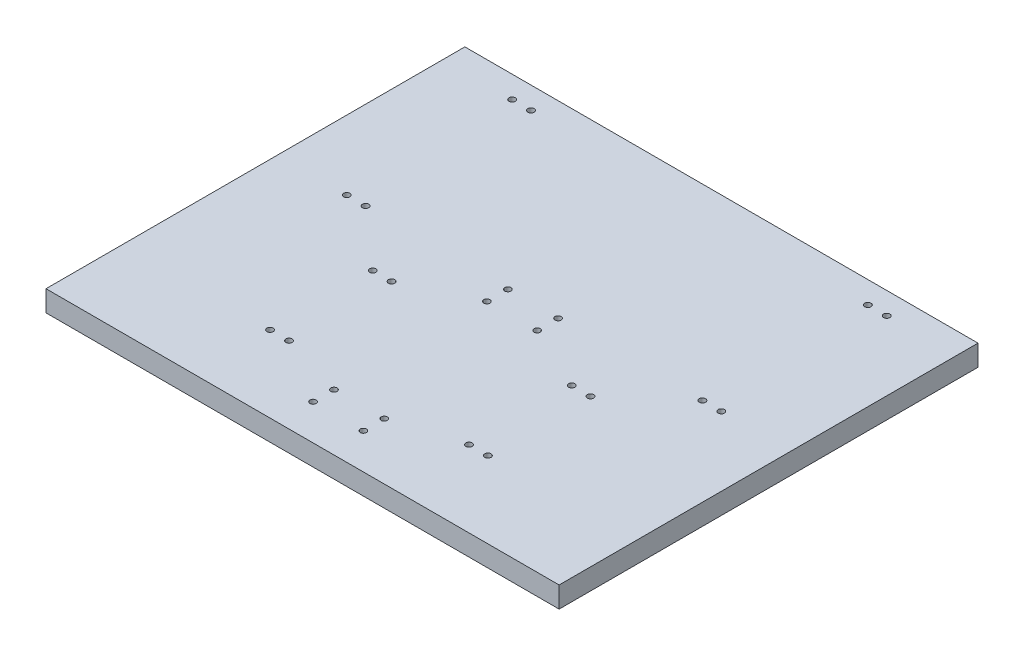
SolidWorks part; units mm, degrees
ref_plane "Front Plane" through (0, 0, 0) normal (0, 0, 1) x (1, 0, 0)
ref_plane "Top Plane" through (0, 0, 0) normal (0, 1, 0) x (1, 0, 0)
ref_plane "Right Plane" through (0, 0, 0) normal (1, 0, 0) x (0, 0, -1)
sketch "Sketch1" plane through (0, 0, 0) normal (0, 1, 0) x (1, 0, 0)
  line L0 (88.8314, 200) -> (88.8314, 0) construction
  line L1 (0, 0) -> (122.5, 0)
  line L2 (0, 0) -> (0, 200)
  line L3 (0, 200) -> (122.5, 200)
  line L4 (122.5, 0) -> (122.5, 200)
  line L5 (0, 175.2721) -> (122.5, 175.2721) construction
  line L6 (0, 123.5936) -> (122.5, 123.5936) construction
  dimension "D1" = 122.5
  dimension "D2" = 200
extrude "Boss-Extrude1" add sketch "Sketch1" along normal blind 10
sketch "Sketch4" plane through (0, 10, 0) normal (0, 1, 0) x (1, 0, 0)
  line L0 (0, 189.5) -> (122.5, 189.5) construction
  line L1 (0, 200) -> (0, 0) construction
  line L2 (122.5, 0) -> (122.5, 200) construction
  line L3 (0, 110.5) -> (122.5, 110.5) construction
  line L4 (37.575, 200) -> (37.575, 0) construction
  line L5 (122.5, 200) -> (0, 200) construction
  line L6 (0, 0) -> (122.5, 0) construction
  line L7 (75, 200) -> (75, 0) construction
  line L8 (0, 85.5) -> (122.5, 85.5) construction
  line L9 (0, 36.5) -> (122.5, 36.5) construction
  circle A0 centre (33.075, 189.5) radius 1.5
  circle A1 centre (42.075, 189.5) radius 1.5
  circle A2 centre (33.075, 110.5) radius 1.5
  circle A3 centre (42.075, 110.5) radius 1.5
  circle A4 centre (70.5, 85.5) radius 1.5
  circle A5 centre (79.5, 85.5) radius 1.5
  circle A6 centre (70.5, 36.5) radius 1.5
  circle A7 centre (79.5, 36.5) radius 1.5
  dimension "D6" = 3
  dimension "D1" = 10.5
  dimension "D2" = 79
  dimension "D3" = 37.575
  dimension "D4" = 4.5
  dimension "D5" = 4.5
  dimension "D7" = 75
  dimension "D8" = 49
  dimension "D9" = 25
  dimension "D10" = 4.5
  dimension "D11" = 4.5
extrude "Cut-Extrude2" cut sketch "Sketch4" against normal blind 10
mirror "Mirror1" about plane through (122.5, 10, 0) normal (-1, 0, 0) of bodies 103
sketch "Sketch5" plane through (0, 10, 0) normal (0, 1, 0) x (1, 0, 0)
  line L0 (0, 22) -> (245, 22) construction
  line L1 (0, 200) -> (0, 0) construction
  line L2 (245, 200) -> (245, 0) construction
  line L3 (0, 105) -> (245, 105) construction
  line L4 (245, 200) -> (0, 200) construction
  line L5 (0, 0) -> (245, 0) construction
  line L6 (122.5, 200) -> (122.5, 0) construction
  line L7 (0, 110) -> (245, 110) construction
  line L8 (0, 100) -> (245, 100) construction
  line L9 (0, 27) -> (245, 27) construction
  line L10 (0, 17) -> (245, 17) construction
  line L11 (110.5, 200) -> (110.5, 0) construction
  line L12 (134.5, 200) -> (134.5, 0) construction
  circle A0 centre (134.5, 110) radius 1.475
  circle A1 centre (110.5, 110) radius 1.475
  circle A2 centre (110.5, 100) radius 1.475
  circle A3 centre (134.5, 100) radius 1.475
  circle A4 centre (110.5, 27) radius 1.475
  circle A5 centre (134.5, 27) radius 1.475
  circle A6 centre (134.5, 17) radius 1.475
  circle A7 centre (110.5, 17) radius 1.475
  dimension "D9" = 2.95
  dimension "D1" = 95
  dimension "D2" = 22
  dimension "D3" = 5
  dimension "D4" = 5
  dimension "D5" = 5
  dimension "D6" = 5
  dimension "D7" = 12
  dimension "D8" = 12
extrude "Cut-Extrude3" cut sketch "Sketch5" against normal blind 10
